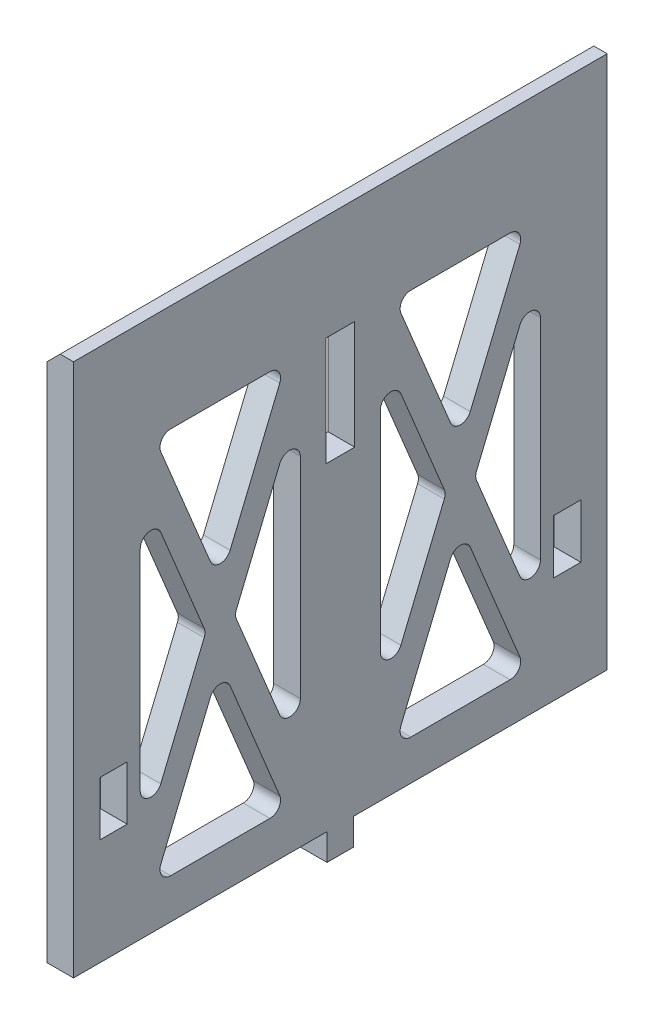
SolidWorks part; units mm, degrees
ref_plane "Front Plane" through (0, 0, 0) normal (0, 0, 1) x (1, 0, 0)
ref_plane "Top Plane" through (0, 0, 0) normal (0, 1, 0) x (1, 0, 0)
ref_plane "Right Plane" through (0, 0, 0) normal (1, 0, 0) x (0, 0, -1)
sketch "Sketch4" plane through (0, 0, 0) normal (1, 0, 0) x (0, 0, -1)
  line L0 (0, 6.35) -> (-60.325, 6.35)
  line L1 (0, 0) -> (6.35, 0)
  line L2 (0, 0) -> (0, 6.35)
  line L3 (0, 6.35) -> (6.35, 6.35) construction
  line L4 (6.35, 0) -> (6.35, 6.35)
  line L5 (6.35, 6.35) -> (66.675, 6.35)
  line L6 (66.675, 6.35) -> (66.675, 32.004)
  line L7 (66.675, 133.35) -> (-60.325, 133.35)
  line L9 (3.175, 6.35) -> (3.175, 177.7936) construction
  line L10 (-0.254, 108.204) -> (6.604, 108.204)
  line L11 (0, 107.95) -> (6.35, 107.95) construction
  line L12 (0, 107.95) -> (0, 82.55) construction
  line L13 (0, 82.55) -> (6.35, 82.55) construction
  line L14 (6.35, 107.95) -> (6.35, 82.55) construction
  line L15 (6.604, 108.204) -> (6.604, 82.296)
  line L16 (-0.254, 82.296) -> (6.604, 82.296)
  line L17 (-0.254, 108.204) -> (-0.254, 82.296)
  line L25 (-60.325, 133.35) -> (-60.325, 44.704)
  line L69 (66.675, 44.704) -> (66.675, 32.004)
  line L70 (53.975, 44.45) -> (53.975, 31.75) construction
  line L71 (60.325, 31.75) -> (53.975, 31.75) construction
  line L72 (60.325, 44.45) -> (60.325, 31.75) construction
  line L73 (-54.0512, 44.5262) -> (-47.5488, 44.5262)
  line L74 (-53.975, 44.45) -> (-47.625, 44.45) construction
  line L75 (-53.975, 44.45) -> (-53.975, 31.75) construction
  line L76 (0, 32.258) -> (6.35, 32.258) construction
  line L77 (60.325, 44.45) -> (53.975, 44.45) construction
  line L78 (60.4012, 44.5262) -> (60.4012, 31.6738)
  line L79 (60.4012, 31.6738) -> (53.8988, 31.6738)
  line L80 (-53.975, 31.75) -> (-47.625, 31.75) construction
  line L81 (-47.625, 44.45) -> (-47.625, 31.75) construction
  line L82 (-47.5488, 44.5262) -> (-47.5488, 31.6738)
  line L83 (-0.254, 32.512) -> (6.604, 32.512)
  line L84 (-60.325, 32.004) -> (-60.325, 6.35)
  line L85 (66.675, 44.704) -> (66.675, 133.35)
  line L86 (-60.325, 44.704) -> (-60.325, 32.004)
  line L87 (-54.0512, 31.6738) -> (-47.5488, 31.6738)
  line L88 (-54.0512, 44.5262) -> (-54.0512, 31.6738)
  line L89 (53.8988, 44.5262) -> (53.8988, 31.6738)
  line L90 (60.4012, 44.5262) -> (53.8988, 44.5262)
  dimension "D1" = 6.35
  dimension "D2" = 6.35
  dimension "D3" = 60.325
  dimension "D4" = 127
  dimension "D5" = 6.35
  dimension "D6" = 25.4
  dimension "D8" = 25.4
  dimension "D19" = 6.35
  dimension "D20" = 12.7
  dimension "D21" = 25.4
  dimension "D22" = 6.35
  dimension "D7" = 0.254
  dimension "D23" = 0.0762
extrude "Boss-Extrude1" add sketch "Sketch4" along normal blind 6.35
sketch "Sketch5" plane through (6.35, 0, 0) normal (1, 0, 0) x (0, 0, -1)
  line L1 (-44.45, 107.95) -> (50.8, 107.95)
  line L2 (-44.45, 107.95) -> (-44.45, 15.875)
  line L3 (-44.45, 15.875) -> (50.8, 15.875)
  line L4 (50.8, 107.95) -> (50.8, 15.875)
  line L8 (3.175, 107.95) -> (3.175, 15.875) construction
  line L10 (-6.35, 107.95) -> (-6.35, 15.875)
  line L12 (12.7, 107.95) -> (12.7, 15.875)
  line L13 (12.7, 15.875) -> (50.8, 107.95) construction
  line L14 (9.7662, 17.089) -> (47.8662, 109.164)
  line L15 (15.6338, 14.661) -> (53.7338, 106.736)
  line L16 (50.8, 15.875) -> (12.7, 107.95) construction
  line L17 (47.8662, 14.661) -> (9.7662, 106.736)
  line L18 (53.7338, 17.089) -> (15.6338, 109.164)
  line L19 (-6.35, 15.875) -> (-44.45, 107.95) construction
  line L20 (-3.4162, 17.089) -> (-41.5162, 109.164)
  line L21 (-9.2838, 14.661) -> (-47.3838, 106.736)
  line L22 (-44.45, 15.875) -> (-6.35, 107.95) construction
  line L23 (-41.5162, 14.661) -> (-3.4162, 106.736)
  line L24 (-47.3838, 17.089) -> (-9.2838, 109.164)
  line L25 (66.675, 6.35) -> (66.675, 133.35) construction
  line L26 (66.675, 133.35) -> (-60.325, 133.35) construction
  line L27 (-60.325, 133.35) -> (-60.325, 6.35) construction
  line L28 (0, 6.35) -> (-60.325, 6.35) construction
  arc A0 (9.7662, 17.089) -> (15.6338, 14.661) centre (12.7, 15.875) ccw
  arc A1 (53.7338, 106.736) -> (47.8662, 109.164) centre (50.8, 107.95) ccw
  arc A2 (47.8662, 14.661) -> (53.7338, 17.089) centre (50.8, 15.875) ccw
  arc A3 (15.6338, 109.164) -> (9.7662, 106.736) centre (12.7, 107.95) ccw
  arc A4 (-3.4162, 17.089) -> (-9.2838, 14.661) centre (-6.35, 15.875) cw
  arc A5 (-47.3838, 106.736) -> (-41.5162, 109.164) centre (-44.45, 107.95) cw
  arc A6 (-41.5162, 14.661) -> (-47.3838, 17.089) centre (-44.45, 15.875) cw
  arc A7 (-9.2838, 109.164) -> (-3.4162, 106.736) centre (-6.35, 107.95) cw
  point P18 (31.75, 61.9125)
  point P23 (31.75, 61.9125)
  point P28 (-25.4, 61.9125)
  point P33 (-25.4, 61.9125)
  dimension "D6" = 3.175
  dimension "D1" = 15.875
  dimension "D2" = 25.4
  dimension "D3" = 15.875
  dimension "D4" = 9.525
  dimension "D5" = 19.05
extrude "Cut-Extrude1" cut sketch "Sketch5" against normal through all contours L2 L24 L21 | L20 L24 L1 | L23 L3 L21 | L14 L17 L12 | L18 L14 L1 | L18 L4 L15 | L3 L17 L15 | L23 L20 L10
fillet "Fillet1" radius 2.54 24 edges at (3.175, 53.6086, 25.4) (3.175, 15.875, 9.7861) (3.175, 15.875, 41.0139) (3.175, 99.6461, 6.35) (3.175, 24.1789, 6.35) (3.175, 61.9125, 21.9639) (3.175, 53.6086, -31.75) (3.175, 15.875, -47.3639) (3.175, 15.875, -16.1361) (3.175, 61.9125, -35.1861) (3.175, 99.6461, -50.8) (3.175, 24.1789, -50.8) (3.175, 61.9125, 28.8361) (3.175, 24.1789, 44.45) (3.175, 99.6461, 44.45) (3.175, 107.95, -16.1361) (3.175, 107.95, -47.3639) (3.175, 70.2164, -31.75) (3.175, 107.95, 9.7861) (3.175, 70.2164, 25.4) (3.175, 99.6461, -12.7) (3.175, 61.9125, -28.3139) (3.175, 24.1789, -12.7) (3.175, 107.95, 41.0139)
fillet "Fillet2" [suppressed] radius 2.54
chamfer "Chamfer1" distance 3.175 angle 45 1 edges at (0, 133.35, -3.175)
